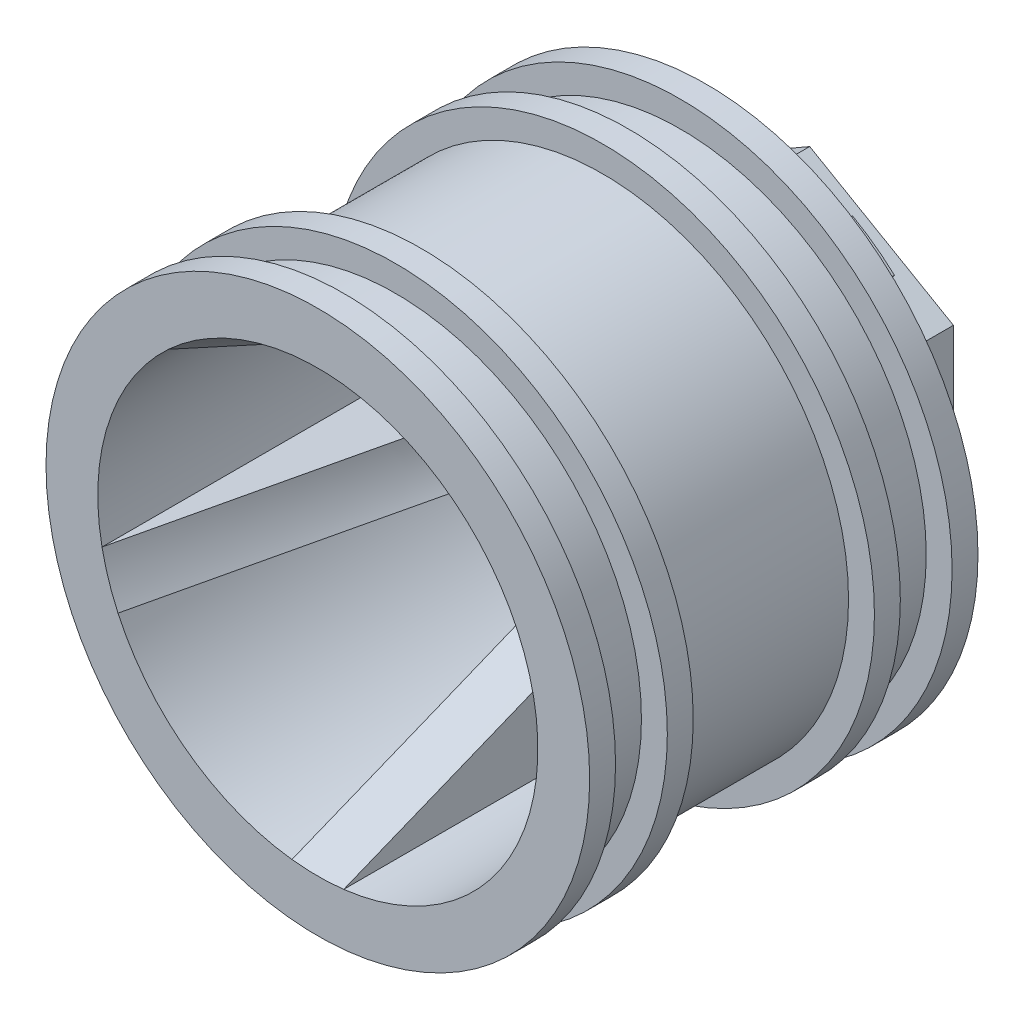
SolidWorks part; units mm, degrees
ref_plane "前视基准面" through (0, 0, 0) normal (0, 0, 1) x (1, 0, 0)
ref_plane "上视基准面" through (0, 0, 0) normal (0, 1, 0) x (1, 0, 0)
ref_plane "右视基准面" through (0, 0, 0) normal (1, 0, 0) x (0, 0, -1)
sketch "草图1" plane through (0, 0, 0) normal (0, 0, 1) x (1, 0, 0)
  circle A0 centre (0, 0) radius 19
  circle A1 centre (0, 0) radius 17
  dimension "D1" = 38
  dimension "D2" = 2
  dimension "D3" = 34
extrude "凸台-拉伸1" add sketch "草图1" along normal blind 30
sketch "草图16" plane through (0, 0, 0) normal (0, 0, -1) x (-1, 0, 0)
  circle A0 centre (0, 0) radius 17
  dimension "D1" = 34
extrude "凸台-拉伸9" add sketch "草图16" along normal blind 3 separate body
sketch "草图4" plane through (0, 0, 0) normal (0, 0, 1) x (1, 0, 0)
  line L0 (0, 0) -> (7.0437, 0) construction
  line L7 (0, 0) -> (0, -50000) construction
  circle A0 centre (0, 0) radius 9
  point P36 (0, 0)
  dimension "D1" = 18
extrude "凸台-拉伸2" add sketch "草图4" along normal blind 10 separate body
sketch "草图6" plane through (0, 0, -3) normal (0, 0, 1) x (1, 0, 0)
  circle A0 centre (0, 0) radius 2.25
  dimension "D1" = 4.5
sketch "草图7" plane through (0, 0, -3) normal (0, 0, -1) x (-1, 0, 0)
  line L0 (0, 0) -> (0, -50000) construction
  line L1 (-2, -8.775) -> (-2, -16.8819)
  line L2 (2, -8.775) -> (2, -16.8819)
  line L3 (-8.9635, -0.8095) -> (-16.6737, -3.3147)
  line L4 (-7.7275, -4.6137) -> (-15.4376, -7.1189)
  line L5 (-3.5398, 8.2747) -> (-8.3049, 14.8333)
  line L6 (-6.7758, 5.9235) -> (-11.541, 12.4822)
  line L7 (6.7758, 5.9235) -> (11.541, 12.4822)
  line L8 (3.5398, 8.2747) -> (8.3049, 14.8333)
  line L9 (7.7275, -4.6137) -> (15.4376, -7.1189)
  line L10 (8.9635, -0.8095) -> (16.6737, -3.3147)
  line L11 (3.5398, 8.2747) -> (6.7758, 5.9235)
  line L12 (6.7758, 5.9235) -> (-3.5398, 8.2747)
  line L13 (-3.5398, 8.2747) -> (-8.9635, -0.8095)
  line L14 (-8.9635, -0.8095) -> (-2, -8.775)
  line L15 (-2, -8.775) -> (7.7275, -4.6137)
  line L16 (7.7275, -4.6137) -> (6.7758, 5.9235)
  line L17 (8.9635, -0.8095) -> (3.5398, 8.2747)
  line L18 (3.5398, 8.2747) -> (-6.7758, 5.9235)
  line L19 (-6.7758, 5.9235) -> (-7.7275, -4.6137)
  line L20 (-7.7275, -4.6137) -> (2, -8.775)
  line L21 (2, -8.775) -> (8.9635, -0.8095)
  circle A0 centre (0, 0) radius 9 construction
  circle A1 centre (0, 0) radius 17 construction
  circle A2 centre (0, 0) radius 9
  circle A3 centre (0, 0) radius 17
  circle A4 centre (0, 0) radius 7.2812 construction
  circle A5 centre (0, 0) radius 7.2812 construction
  point P29 (0, 0)
  circle M31 centre (0, 0) radius 17
  dimension "D4" = 18
  dimension "D2" = 4
  dimension "D3" = 4
  dimension "D1" = 5
extrude "切除-拉伸8" cut sketch "草图7" against normal blind 10 contours A2 L8 L5 M31 | A2 L10 L7 M31 | A2 L2 L9 M31 | A2 L4 L1 M31 | A2 L6 L3 M31
sketch "草图21" plane through (0, 0, 0) normal (0, 0, 1) x (1, 0, 0)
  line L0 (3.5398, 8.2747) -> (8.3049, 14.8333)
  line L1 (6.7758, 5.9235) -> (-3.5398, 8.2747)
  line L2 (-3.5398, 8.2747) -> (-8.9635, -0.8095)
  line L3 (-8.9635, -0.8095) -> (-2, -8.775)
  line L4 (-2, -8.775) -> (7.7275, -4.6137)
  line L5 (7.7275, -4.6137) -> (6.7758, 5.9235)
  line L6 (8.9635, -0.8095) -> (3.5398, 8.2747)
  line L7 (3.5398, 8.2747) -> (-6.7758, 5.9235)
  line L8 (-6.7758, 5.9235) -> (-7.7275, -4.6137)
  line L9 (-7.7275, -4.6137) -> (2, -8.775)
  line L10 (2, -8.775) -> (8.9635, -0.8095)
  line L11 (6.7758, 5.9235) -> (11.541, 12.4822)
  line L13 (8.9635, -0.8095) -> (16.6737, -3.3147)
  line L15 (7.7275, -4.6137) -> (15.4376, -7.1189)
  line L17 (2, -8.775) -> (2, -16.8819)
  line L19 (-2, -8.775) -> (-2, -16.8819)
  line L21 (-7.7275, -4.6137) -> (-15.4376, -7.1189)
  line L22 (-8.9635, -0.8095) -> (-16.6737, -3.3147)
  line L23 (-6.7758, 5.9235) -> (-11.541, 12.4822)
  line L24 (-3.5398, 8.2747) -> (-8.3049, 14.8333)
  circle A0 centre (0, 0) radius 7.2812 construction
  circle A1 centre (0, 0) radius 9 construction
  circle A2 centre (0, 0) radius 7.2812 construction
  circle A3 centre (0, 0) radius 9
  circle A4 centre (0, 0) radius 17
  dimension "D2" = 34
  dimension "D3" = 18
  dimension "D1" = 4
extrude "凸台-拉伸10" add sketch "草图21" along normal blind 30 contours L24 A4 L23 A3 | L11 A4 L0 A3 | L15 A4 L13 A3 | L19 A4 L17 A3 | L22 A4 L21 A3
extrude "切除-拉伸9" cut sketch "草图6" along normal blind 70
sketch "草图9" plane through (0, 0, 0) normal (0, 0, 1) x (1, 0, 0)
  circle A0 centre (0, 0) radius 21
  circle A1 centre (0, 0) radius 19 construction
  circle A2 centre (0, 0) radius 19
  dimension "D1" = 42
extrude "凸台-拉伸4" add sketch "草图9" along normal blind 2
ref_plane "基准面1" through (0, 0, 6) normal (0, 0, 1) x (1, 0, 0)
sketch "草图10" plane through (0, 0, 6) normal (0, 0, 1) x (1, 0, 0)
  circle A2 centre (0, 0) radius 19
  circle A3 centre (0, 0) radius 21
  dimension "D1" = 38
  dimension "D2" = 42
extrude "凸台-拉伸5" add sketch "草图10" along normal blind 2
sketch "草图11" plane through (0, 0, 30) normal (0, 0, 1) x (1, 0, 0)
  circle A0 centre (0, 0) radius 21
  circle A1 centre (0, 0) radius 19
  dimension "D1" = 42
  dimension "D2" = 38
extrude "凸台-拉伸6" add sketch "草图11" against normal blind 2 contours A1 | A0
ref_plane "基准面3" through (0, 0, 24) normal (0, 0, -1) x (-1, 0, 0)
sketch "草图12" plane through (0, 0, 24) normal (0, 0, -1) x (-1, 0, 0)
  circle A0 centre (0, 0) radius 21
  circle A1 centre (0, 0) radius 19
  dimension "D1" = 2
  dimension "D2" = 42
extrude "凸台-拉伸7" add sketch "草图12" along normal blind 2
ref_plane "基准面2" through (0, 0, 20) normal (0, 0, 1) x (1, 0, 0)
sketch "草图13" plane through (0, 0, 10) normal (0, 0, 1) x (1, 0, 0)
  line L7 (-3, 3) -> (3, 3)
  line L8 (-3, 3) -> (-3, -3)
  line L9 (-3, -3) -> (3, -3)
  line L10 (3, 3) -> (3, -3)
  line L11 (-3, 3) -> (3, -3) construction
  line L12 (-3, -3) -> (3, 3) construction
  point P0 (0, 0)
  dimension "D1" = 6
  dimension "D2" = 6
extrude "切除-拉伸5" cut sketch "草图13" against normal blind 2
sketch "草图14" plane through (0, 0, -3) normal (0, 0, -1) x (-1, 0, 0)
  line L12 (-11.1, -6.4086) -> (0, -12.8172)
  line L13 (0, -12.8172) -> (11.1, -6.4086)
  line L14 (11.1, -6.4086) -> (11.1, 6.4086)
  line L15 (11.1, 6.4086) -> (0, 12.8172)
  line L16 (0, 12.8172) -> (-11.1, 6.4086)
  line L17 (-11.1, 6.4086) -> (-11.1, -6.4086)
  circle A0 centre (0, 0) radius 11.1 construction
  circle A1 centre (0, 0) radius 2.15
  dimension "D2" = 4.3
  dimension "D1" = 22.2
extrude "凸台-拉伸11" add sketch "草图14" along normal blind 5
sketch "草图22" plane through (0, 0, -8) normal (0, 0, -1) x (-1, 0, 0)
  circle A0 centre (0, 0) radius 6.15
  dimension "D1" = 12.3
extrude "切除-拉伸10" cut sketch "草图22" against normal blind 4
ref_plane "基准面13" through (0, 0, 8) normal (0, 0, -1) x (-1, 0, 0)
sketch "草图25" plane through (0, 0, -4) normal (0, 0, -1) x (-1, 0, 0)
  circle A0 centre (0, 0) radius 4.5
  dimension "D1" = 9
extrude "切除-拉伸11" cut sketch "草图25" against normal blind 2
sketch "草图27" plane through (0, 0, -3) normal (0, 0, -1) x (-1, 0, 0)
  line L0 (0, 0) -> (-16.168, -5.2533)
  arc A0 (-16.6737, -3.3147) -> (-15.4376, -7.1189) centre (0, 0) ccw construction
ref_plane "基准面14" through (0, 0, 0) normal (-0.309, -0.9511, 0) x (0.9511, -0.309, 0)
sketch "草图28" plane through (0, 0, 0) normal (-0.309, -0.9511, 0) x (0.9511, -0.309, 0)
  line L0 (17, 30) -> (9, 10)
  line L1 (9, 10) -> (17, 10)
  line L2 (17, 10) -> (17, 30)
  line L3 (-14.8333, 30) -> (-17, 30) construction
  line L5 (9, 10) -> (8.775, 10) construction
  line L6 (0, 0) -> (0, 30)
  line L7 (21, 30) -> (-21, 30) construction
  line L8 (9, 10) -> (9, 30)
  line L9 (9, 30) -> (17, 30)
  line L10 (16.8819, 30) -> (7.1189, 30) construction
  dimension "D1" = 9
  dimension "D2" = 17
revolve "切除-旋转1" cut sketch "草图28" angle 360 about L6
sketch "草图29" plane through (0, 0, -8) normal (0, 0, -1) x (-1, 0, 0)
  line L1 (-11.1, 6.4086) -> (11.1, 6.4086)
  dimension "D1" = 22.2
